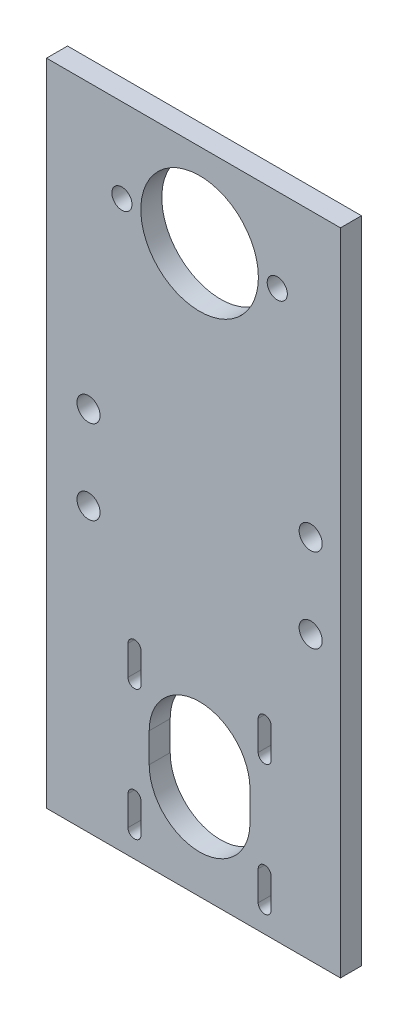
SolidWorks part; units mm, degrees
ref_plane "Front Plane" through (0, 0, 0) normal (0, 0, 1) x (1, 0, 0)
ref_plane "Top Plane" through (0, 0, 0) normal (0, 1, 0) x (1, 0, 0)
ref_plane "Right Plane" through (0, 0, 0) normal (1, 0, 0) x (0, 0, -1)
sketch "Sketch1" plane through (0, 0, 0) normal (0, 0, 1) x (1, 0, 0)
  line L0 (-26.4505, -10) -> (26.4505, 10) construction
  line L2 (-36.4505, -77.3566) -> (-36.4505, 77.3566)
  line L3 (-36.4505, 77.3566) -> (33.5495, 77.3566)
  line L4 (33.5495, -77.3566) -> (33.5495, 77.3566)
  line L5 (-26.4505, 10) -> (26.4505, -10) construction
  line L6 (-36.4505, -77.3566) -> (33.5495, -77.3566)
  line L7 (-18.5, 57.3566) -> (18.5, 57.3566) construction
  line L8 (-15.5, -33.6434) -> (-15.5, -40.6434) construction
  line L9 (-15.5, -68.1434) -> (15.5, -68.1434) construction
  line L11 (-15.5, -68.1434) -> (-15.5, -37.1434) construction
  line L14 (-15.5, -37.1434) -> (15.5, -37.1434) construction
  line L15 (15.5, -68.1434) -> (15.5, -37.1434) construction
  line L16 (-15.5, -68.1434) -> (15.5, -37.1434) construction
  line L17 (-15.5, -37.1434) -> (15.5, -68.1434) construction
  line L18 (-13.95, -33.6434) -> (-13.95, -40.6434)
  line L19 (-17.05, -33.6434) -> (-17.05, -40.6434)
  line L20 (15.5, -33.6434) -> (15.5, -40.6434) construction
  line L21 (17.05, -33.6434) -> (17.05, -40.6434)
  line L22 (13.95, -33.6434) -> (13.95, -40.6434)
  line L23 (15.5, -64.6434) -> (15.5, -71.6434) construction
  line L24 (17.05, -64.6434) -> (17.05, -71.6434)
  line L25 (13.95, -64.6434) -> (13.95, -71.6434)
  line L26 (-15.5, -64.6434) -> (-15.5, -71.6434) construction
  line L27 (-13.95, -64.6434) -> (-13.95, -71.6434)
  line L28 (-17.05, -64.6434) -> (-17.05, -71.6434)
  line L29 (0, -56.1434) -> (0, -49.1434) construction
  line L30 (-12, -56.1434) -> (-12, -49.1434)
  line L31 (12, -56.1434) -> (12, -49.1434)
  circle A0 centre (-18.5, 57.3566) radius 2.4
  circle A1 centre (18.5, 57.3566) radius 2.4
  circle A2 centre (0, 57.3566) radius 5
  circle A3 centre (-26.4505, 10) radius 2.75
  circle A4 centre (26.4505, 10) radius 2.75
  circle A5 centre (26.4505, -10) radius 2.75
  circle A6 centre (-26.4505, -10) radius 2.75
  circle A7 centre (0, 57.3566) radius 14
  arc A13 (-13.95, -33.6434) -> (-17.05, -33.6434) centre (-15.5, -33.6434) ccw
  arc A14 (-17.05, -40.6434) -> (-13.95, -40.6434) centre (-15.5, -40.6434) ccw
  arc A15 (17.05, -33.6434) -> (13.95, -33.6434) centre (15.5, -33.6434) ccw
  arc A16 (13.95, -40.6434) -> (17.05, -40.6434) centre (15.5, -40.6434) ccw
  arc A17 (17.05, -64.6434) -> (13.95, -64.6434) centre (15.5, -64.6434) ccw
  arc A18 (13.95, -71.6434) -> (17.05, -71.6434) centre (15.5, -71.6434) ccw
  arc A19 (-13.95, -64.6434) -> (-17.05, -64.6434) centre (-15.5, -64.6434) ccw
  arc A20 (-17.05, -71.6434) -> (-13.95, -71.6434) centre (-15.5, -71.6434) ccw
  arc A21 (-12, -56.1434) -> (12, -56.1434) centre (0, -56.1434) ccw
  arc A22 (12, -49.1434) -> (-12, -49.1434) centre (0, -49.1434) ccw
  point P0 (0, 0)
  point P5 (-36.4505, 0)
  point P6 (0, -52.6434)
  point P25 (-15.5, -37.1434)
  point P38 (15.5, -37.1434)
  point P45 (15.5, -68.1434)
  point P52 (-15.5, -68.1434)
  point P57 (0, -52.6434)
  dimension "D4" = 4.8
  dimension "D5" = 10
  dimension "D6" = 5.5
  dimension "D11" = 28
  dimension "D7" = 12
  dimension "D12" = 1.55
  dimension "D1" = 70
  dimension "D2" = 31
  dimension "D3" = 37
  dimension "D8" = 20
  dimension "D9" = 7
  dimension "D10" = 20
  dimension "D13" = 110
  dimension "D14" = 7
extrude "Boss-Extrude1" add sketch "Sketch1" along normal blind 5
